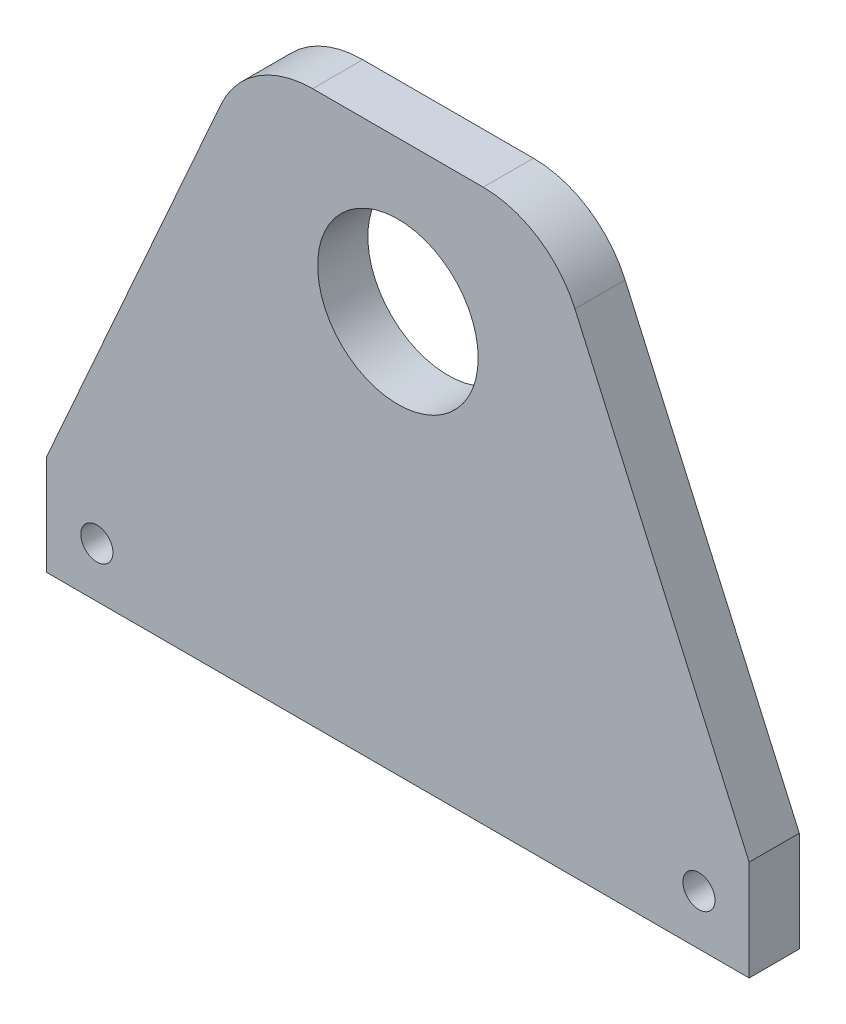
SolidWorks part; units mm, degrees
ref_plane "Front Plane" through (0, 0, 0) normal (0, 0, 1) x (1, 0, 0)
ref_plane "Top Plane" through (0, 0, 0) normal (0, 1, 0) x (1, 0, 0)
ref_plane "Right Plane" through (0, 0, 0) normal (1, 0, 0) x (0, 0, -1)
sketch "ｽｹｯﾁ1" plane through (0, 0, 0) normal (0, 0, 1) x (1, 0, 0)
  line L0 (0, 0) -> (0, 10)
  line L1 (0, 10) -> (20, 55)
  line L2 (20, 55) -> (50, 55)
  line L3 (50, 55) -> (70, 10)
  line L4 (70, 10) -> (70, 0)
  line L5 (70, 0) -> (0, 0)
  circle A0 centre (35, 40) radius 8
  circle A1 centre (5, 5) radius 1.6
  circle A2 centre (65, 5) radius 1.6
  point P13 (35, 55)
  point P14 (35, 0)
  dimension "D5" = 16
  dimension "D6" = 15
  dimension "D9" = 0
  dimension "D10" = 3.2
  dimension "D11" = 5
  dimension "D12" = 5
  dimension "D14" = 3.2
  dimension "D15" = 5
  dimension "D1" = 70
  dimension "D2" = 10
  dimension "D3" = 10
  dimension "D4" = 55
  dimension "D7" = 0
  dimension "D8" = 30
  dimension "D13" = 5
extrude "ﾎﾞｽ - 押し出し1" add sketch "ｽｹｯﾁ1" along normal blind 5
fillet "ﾌｨﾚｯﾄ1" radius 10 2 edges at (20, 55, 2.5) (50, 55, 2.5)
